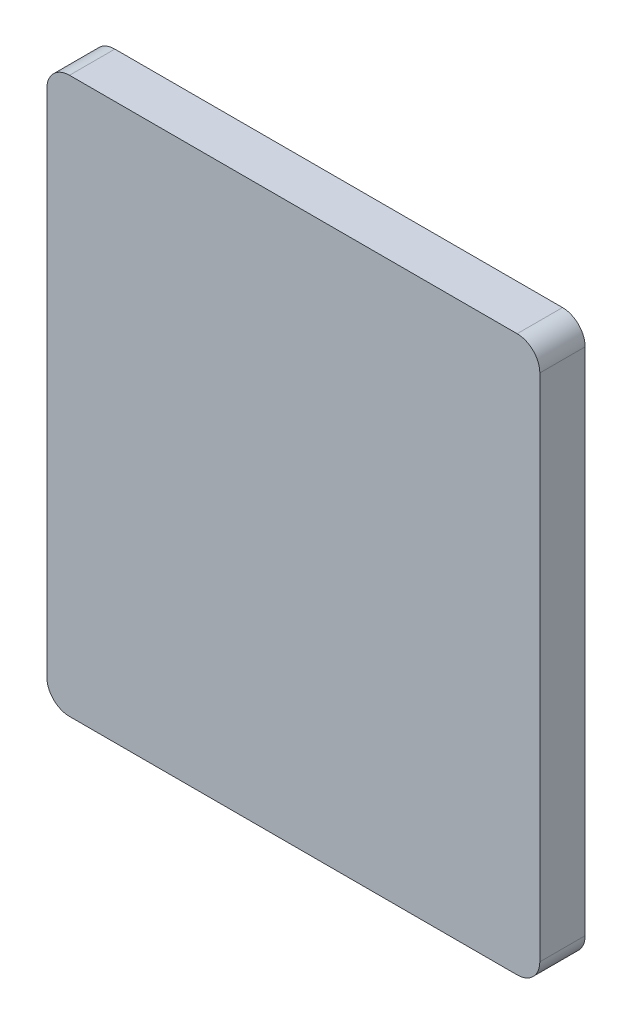
SolidWorks part; units mm, degrees
material "Glass"
ref_plane "Front Plane" through (0, 0, 0) normal (0, 0, 1) x (1, 0, 0)
ref_plane "Top Plane" through (0, 0, 0) normal (0, 1, 0) x (1, 0, 0)
ref_plane "Right Plane" through (0, 0, 0) normal (1, 0, 0) x (0, 0, -1)
sketch "Sketch1" plane through (0, 0, 0) normal (0, 0, 1) x (1, 0, 0)
  line L1 (39.5, -49) -> (-39.5, -49)
  line L2 (43.5, -45) -> (43.5, 45)
  line L3 (39.5, 49) -> (-39.5, 49)
  line L4 (-43.5, -45) -> (-43.5, 45)
  line L5 (43.5, -49) -> (-43.5, 49) construction
  line L6 (43.5, 49) -> (-43.5, -49) construction
  arc A0 (43.5, 45) -> (39.5, 49) centre (39.5, 45) ccw
  arc A1 (43.5, -45) -> (39.5, -49) centre (39.5, -45) cw
  arc A2 (-43.5, -45) -> (-39.5, -49) centre (-39.5, -45) ccw
  arc A3 (-43.5, 45) -> (-39.5, 49) centre (-39.5, 45) cw
  point P0 (0, 0)
  dimension "D3" = 4
  dimension "D1" = 87
  dimension "D2" = 98
extrude "Boss-Extrude1" add sketch "Sketch1" along normal blind 8
